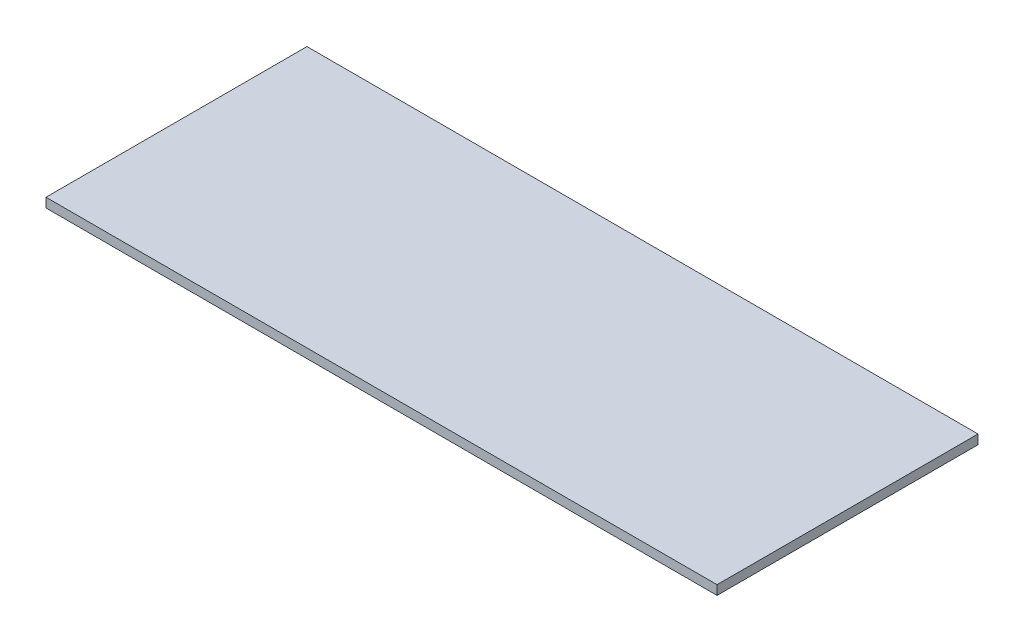
SolidWorks part; units mm, degrees
material "Acrylic (Medium-high impact)"
ref_plane "Front Plane" through (0, 0, 0) normal (0, 0, 1) x (1, 0, 0)
ref_plane "Top Plane" through (0, 0, 0) normal (0, 1, 0) x (1, 0, 0)
ref_plane "Right Plane" through (0, 0, 0) normal (1, 0, 0) x (0, 0, -1)
sketch "Sketch1" plane through (0, 0, 0) normal (0, 1, 0) x (1, 0, 0)
  line L1 (-228.6, -88.9) -> (228.6, -88.9)
  line L2 (-228.6, -88.9) -> (-228.6, 88.9)
  line L3 (-228.6, 88.9) -> (228.6, 88.9)
  line L4 (228.6, -88.9) -> (228.6, 88.9)
  line L5 (-228.6, -88.9) -> (228.6, 88.9) construction
  line L6 (-228.6, 88.9) -> (228.6, -88.9) construction
  point P0 (0, 0)
  dimension "D1" = 457.2
  dimension "D2" = 177.8
extrude "Boss-Extrude1" add sketch "Sketch1" along normal blind 6.35 contours L3 L4 L1 L2
equation "\"high\"= 7in"
equation "\"wide\" = 18in"
equation "\"thick\"= 0.25in"
equation "\"D1@Sketch1\"=\"wide\""
equation "\"D2@Sketch1\"=\"high\""
equation "\"D1@Boss-Extrude1\"=\"thick\""
